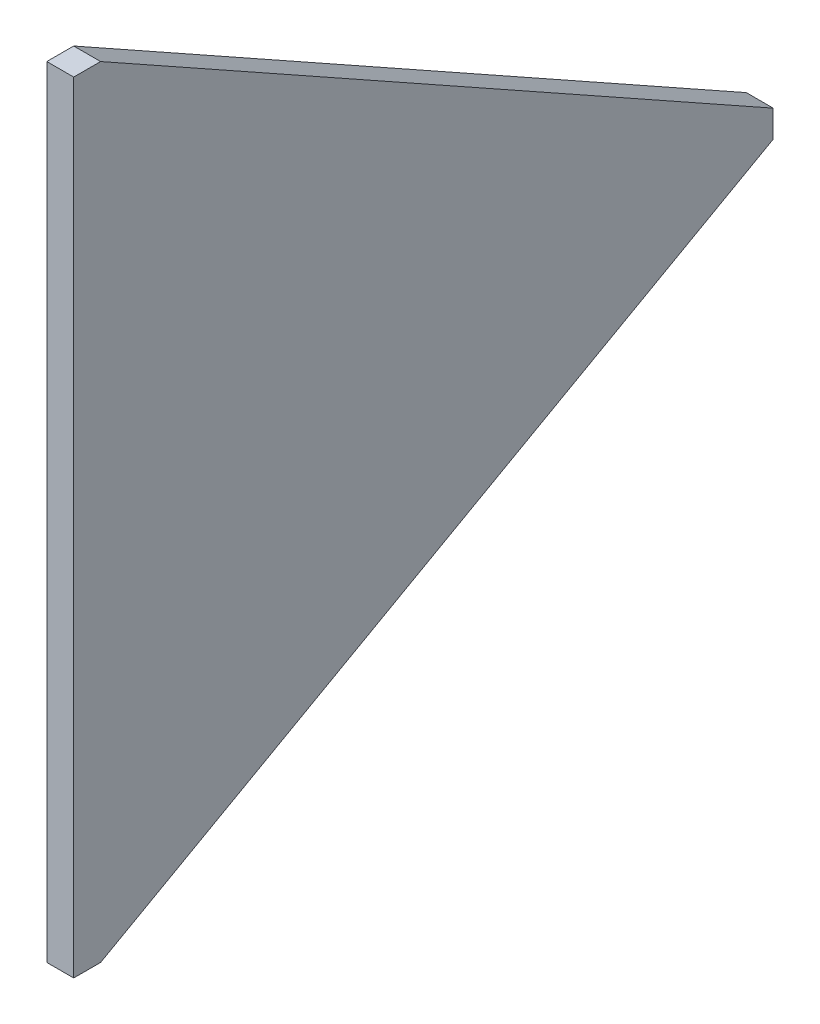
SolidWorks part; units mm, degrees
ref_plane "Front Plane" through (0, 0, 0) normal (0, 0, 1) x (1, 0, 0)
ref_plane "Top Plane" through (0, 0, 0) normal (0, 1, 0) x (1, 0, 0)
ref_plane "Right Plane" through (0, 0, 0) normal (1, 0, 0) x (0, 0, -1)
sketch "Sketch1" plane through (0, 0, 0) normal (1, 0, 0) x (0, 0, -1)
  line L0 (0, 29) -> (0, -29)
  line L1 (0, -29) -> (2, -29)
  line L2 (2, -29) -> (52, -1)
  line L3 (52, -1) -> (52, 1)
  line L4 (52, 1) -> (2, 29)
  line L5 (2, 29) -> (0, 29)
  point P0 (52, 0)
  point P4 (0, 0)
  dimension "D1" = 2
  dimension "D2" = 50
  dimension "D3" = 58
extrude "Boss-Extrude1" add sketch "Sketch1" along normal blind 2
